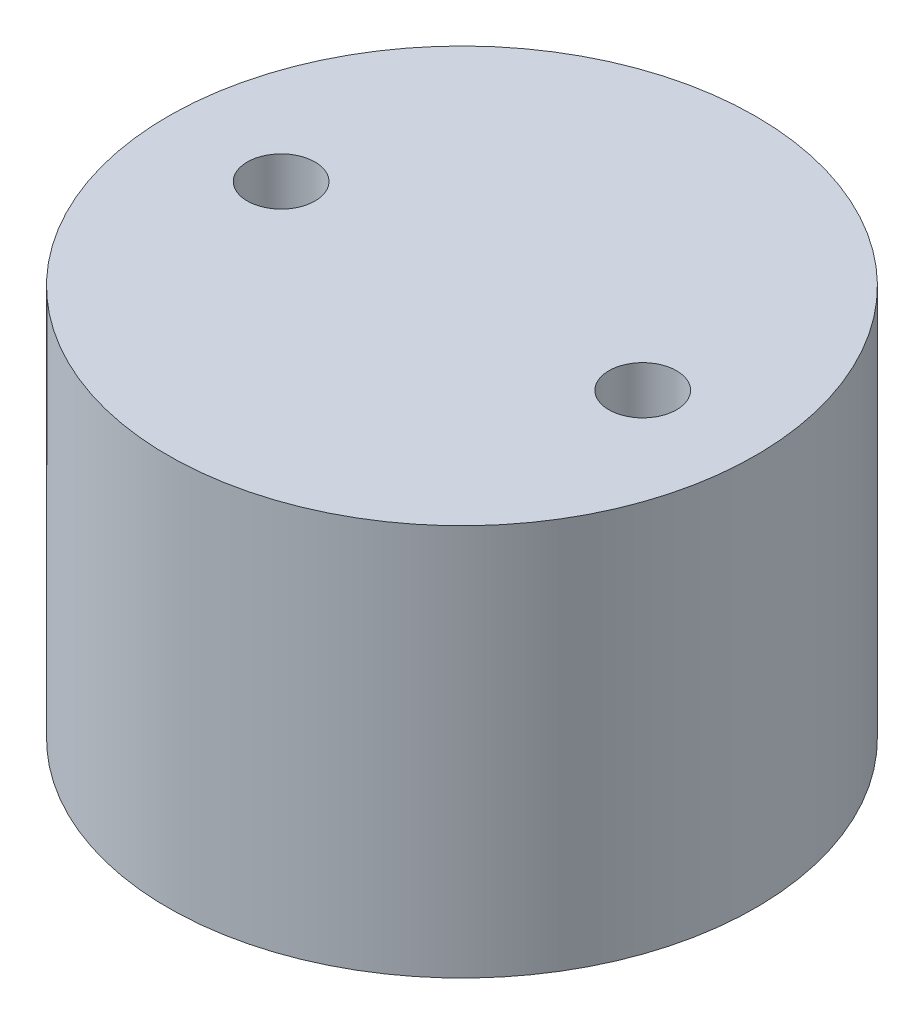
SolidWorks part; units mm, degrees
ref_plane "Front Plane" through (0, 0, 0) normal (0, 0, 1) x (1, 0, 0)
ref_plane "Top Plane" through (0, 0, 0) normal (0, 1, 0) x (1, 0, 0)
ref_plane "Right Plane" through (0, 0, 0) normal (1, 0, 0) x (0, 0, -1)
sketch "Sketch1" plane through (0, 0, 0) normal (0, 1, 0) x (1, 0, 0)
  circle A0 centre (0, 0) radius 19.5
  dimension "D1" = 39
extrude "Boss-Extrude1" add sketch "Sketch1" along normal blind 26
hole_wizard "CSK for #8 Flat Head Machine Screw (100)1" positions "Sketch4" profile "Sketch3" countersink size "#8" standard "ANSI Inch" end condition through all
sketch "Sketch4" plane through (0, 0, 0) normal (0, -1, 0) x (-1, 0, 0)
  line L0 (0, 0) -> (0, 7.7783) construction
  point P0 (-12, 0)
  point P2 (12, 0)
  dimension "D1" = 24
sketch "Sketch3" plane through (12, 0, 0) normal (1, 0, 0) x (0, 0, -1)
  line L0 (0, 0) -> (0, 26)
  line L1 (0, 26) -> (2.2479, 26)
  line L2 (2.2479, 26) -> (2.2479, 11.6518)
  line L3 (2.2479, 11.6518) -> (4.2164, 10)
  line L4 (4.2164, 10) -> (4.2164, 0)
  line L6 (4.2164, 0) -> (0, 0)
  line L7 (-2.2479, 11.6518) -> (-4.2164, 10) construction
  line L11 (0, -6.35) -> (0, 107.95) construction
  dimension "Thru Hole Dia." = 4.4958
  dimension "Thru Hole Depth" = 26
  dimension "C'Sink Dia." = 8.4328
  dimension "C'Sink Angle" = 100
  dimension "Head Clearance" = 10
